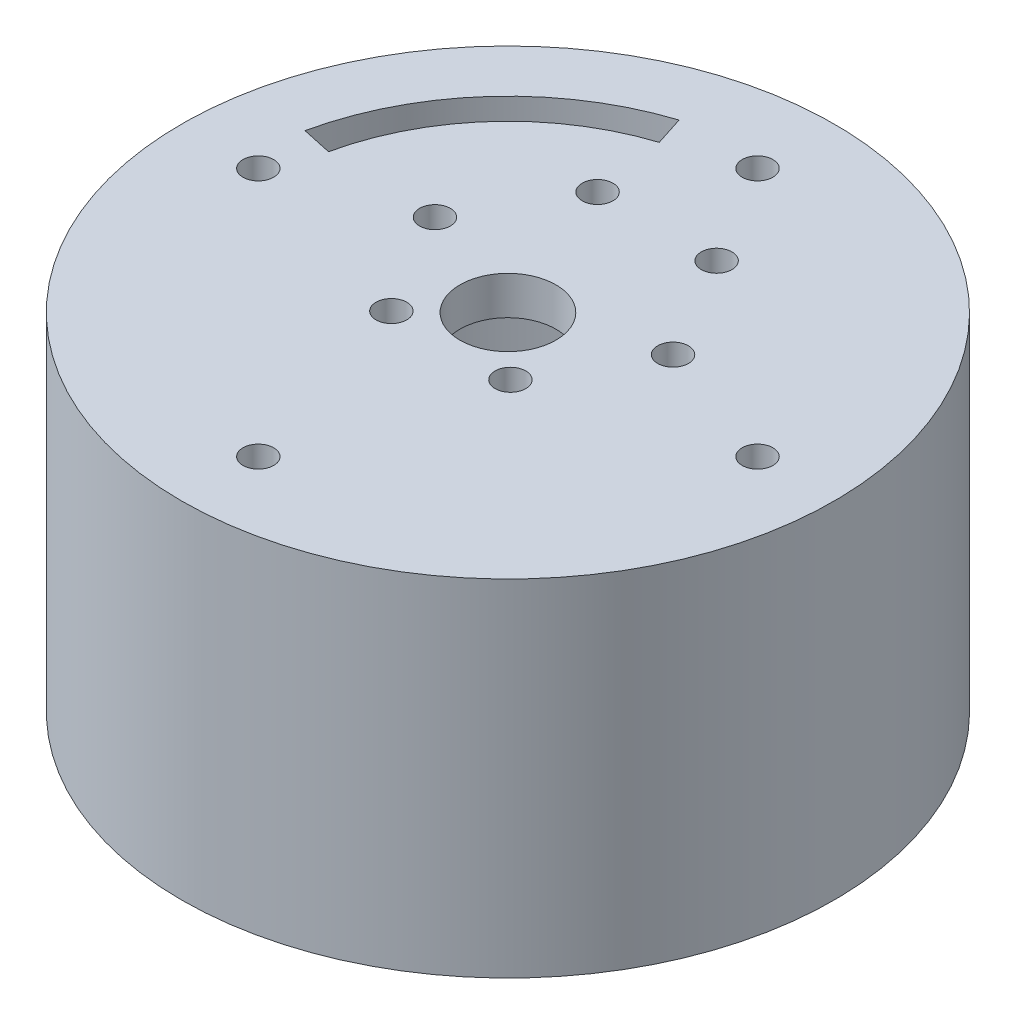
SolidWorks part; units mm, degrees
ref_plane "Ön Düzlem" through (0, 0, 0) normal (0, 0, 1) x (1, 0, 0)
ref_plane "Üst Düzlem" through (0, 0, 0) normal (0, 1, 0) x (1, 0, 0)
ref_plane "Sağ Düzlem" through (0, 0, 0) normal (1, 0, 0) x (0, 0, -1)
sketch "Çizim6" plane through (0, 0, 0) normal (0, 1, 0) x (1, 0, 0)
  circle A0 centre (0, 0) radius 42.5
  circle A1 centre (0, 0) radius 38
extrude "Yükseklik-Ekstrüzyon1" add sketch "Çizim6" along normal blind 40
sketch "Çizim7" plane through (0, 40, 0) normal (0, 1, 0) x (1, 0, 0)
  circle A0 centre (0, 0) radius 42.5
extrude "Yükseklik-Ekstrüzyon2" add sketch "Çizim7" along normal blind 5
sketch "Çizim8" plane through (0, 45, 0) normal (0, 1, 0) x (1, 0, 0)
  circle A10 centre (0, 32.5) radius 2
  circle A11 centre (-32.5, 0) radius 2
  circle A12 centre (32.5, 0) radius 2
  circle A13 centre (0, -32.5) radius 2
  circle A14 centre (0, 0) radius 6.25
  circle A16 centre (-15.5, 6) radius 2
  circle A17 centre (-7.75, 19.4234) radius 2
  circle A18 centre (7.75, 19.4234) radius 2
  circle A19 centre (15.5, 6) radius 2
  circle A20 centre (7.75, -7.4234) radius 2
  circle A21 centre (-7.75, -7.4234) radius 2
  dimension "D1" = 12.5
  dimension "D2" = 4
extrude "Kes-Ekstrüzyon2" cut sketch "Çizim8" against normal blind 5
sketch "Çizim11" plane through (0, 45, 0) normal (0, 1, 0) x (1, 0, 0)
  line L0 (-33.7199, 7.2952) -> (-29.8103, 6.4494)
  line L1 (-10.5613, 32.8437) -> (-9.3368, 29.0357)
  arc A0 (-10.5613, 32.8437) -> (-33.7199, 7.2952) centre (0, 0) ccw
  arc A1 (-9.3368, 29.0357) -> (-29.8103, 6.4494) centre (0, 0) ccw
extrude "Kes-Ekstrüzyon4" cut sketch "Çizim11" against normal blind 5
